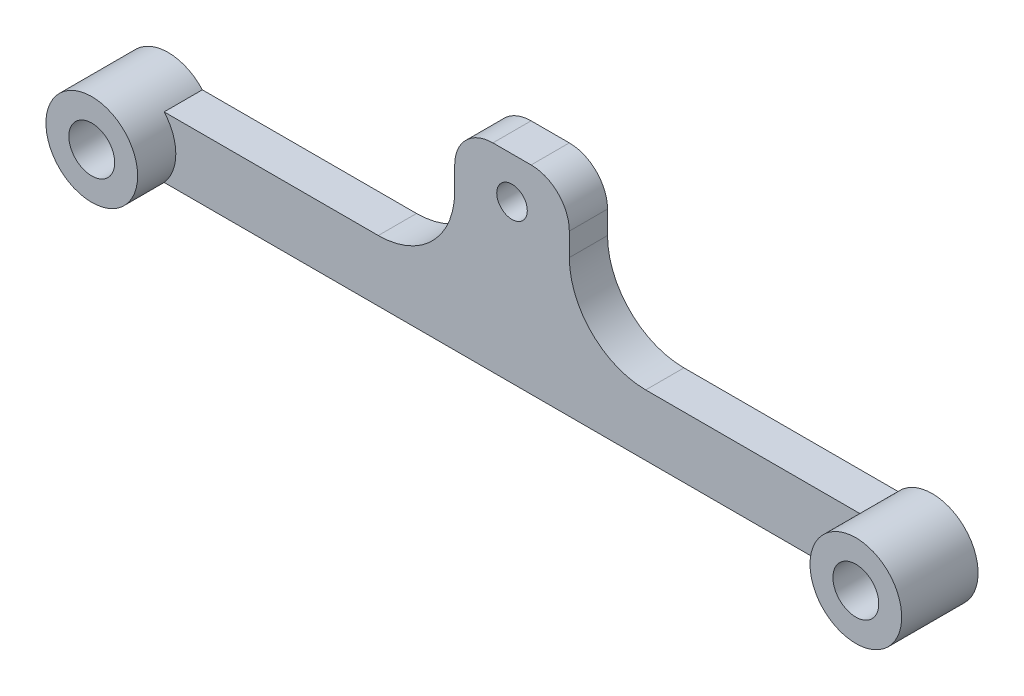
SolidWorks part; units mm, degrees
ref_plane "前视基准面" through (0, 0, 0) normal (0, 0, 1) x (1, 0, 0)
ref_plane "上视基准面" through (0, 0, 0) normal (0, 1, 0) x (1, 0, 0)
ref_plane "右视基准面" through (0, 0, 0) normal (1, 0, 0) x (0, 0, -1)
other "Configuration Table"
sketch "草图1" plane through (0, 0, 0) normal (0, 0, 1) x (1, 0, 0)
  circle A0 centre (0, 0) radius 6
  dimension "D1" = 12
extrude "凸台-拉伸1" add sketch "草图1" along normal blind 10
sketch "草图3" plane through (0, 0, 0) normal (1, 0, 0) x (0, 0, -1)
  line L0 (0, -6) -> (0, 6) construction
  line L1 (0, 4) -> (-5, 4)
  line L2 (0, 4) -> (0, -4)
  line L3 (0, -4) -> (-5, -4)
  line L4 (-5, 4) -> (-5, -4)
  line L5 (-10, 0) -> (0, 0) construction
  dimension "D1" = 5
  dimension "D2" = 8
  dimension "D3" = 4
extrude "凸台-拉伸2" add sketch "草图3" along normal blind 50
sketch "草图2" plane through (0, 0, 10) normal (0, 0, 1) x (1, 0, 0)
  circle A0 centre (0, 0) radius 3
  dimension "D1" = 6
extrude "切除-拉伸1" cut sketch "草图2" against normal blind 30
mirror "镜向1" about plane through (50, 0, 0) normal (-1, 0, 0) of bodies 107
sketch "草图14" plane through (0, 0, 0) normal (0, 0, -1) x (-1, 0, 0)
  line L0 (-50, 4) -> (-50, 26.6789) construction
  line L6 (-95.5279, 4) -> (-4.4721, 4) construction
  line L7 (-57.5, 4) -> (-57.5, 22)
  line L8 (-57.5, 22) -> (-42.5, 22)
  line L9 (-42.5, 22) -> (-42.5, 4)
  line L10 (-42.5, 4) -> (-57.5, 4)
  dimension "D1" = 18
  dimension "D2" = 15
  dimension "D3" = 7.5
extrude "凸台-拉伸7" add sketch "草图14" against normal up to surface (5 mm away) up to face at (50, 0, 5)
sketch "草图15" plane through (0, 0, 0) normal (0, 0, -1) x (-1, 0, 0)
  line L0 (-57.5, 4) -> (-42.5, 4) construction
  line L1 (-50, 4) -> (-50, 23.7541) construction
  circle A1 centre (-50, 16.57) radius 2
  dimension "D1" = 4
  dimension "D2" = 12.57
fillet "圆角2" radius 5 2 edges at (57.5, 22, 2.5) (42.5, 22, 2.5)
fillet "圆角3" radius 10 2 edges at (42.5, 4, 2.5) (57.5, 4, 2.5)
extrude "切除-拉伸4" cut sketch "草图15" against normal up to surface (5 mm away) up to face at (50, 9.3274, 5)
